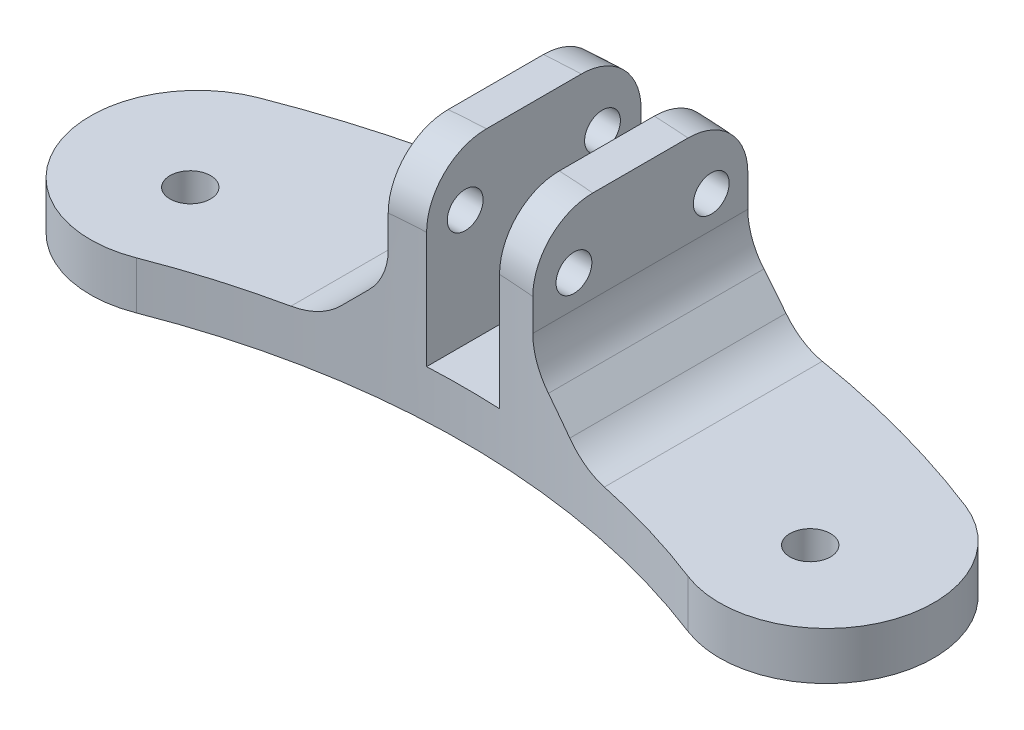
SolidWorks part; units mm, degrees
ref_plane "Front Plane" through (0, 0, 0) normal (0, 0, 1) x (1, 0, 0)
ref_plane "Top Plane" through (0, 0, 0) normal (0, 1, 0) x (1, 0, 0)
ref_plane "Right Plane" through (0, 0, 0) normal (1, 0, 0) x (0, 0, -1)
sketch "Sketch1" plane through (0, 0, 0) normal (0, 1, 0) x (1, 0, 0)
  line L0 (0, 0) -> (0, 66.7905) construction
  line L1 (-25.965, 66.7905) -> (25.965, 66.7905) construction
  line L2 (0, 63.75) -> (0, 81.7) construction
  line L3 (-29.6029, 76.1483) -> (-23.0989, 59.418) construction
  circle A1 centre (-25.965, 66.7905) radius 1.7
  circle A2 centre (25.965, 66.7905) radius 1.7
  arc A3 (-23.0989, 59.418) -> (23.0989, 59.418) centre (0, 0) cw
  arc A4 (-29.6029, 76.1483) -> (29.6029, 76.1483) centre (0, 0) cw
  arc A5 (-29.6029, 76.1483) -> (-23.0989, 59.418) centre (-26.3509, 67.7832) ccw
  arc A6 (29.6029, 76.1483) -> (23.0989, 59.418) centre (26.3509, 67.7832) cw
  point P7 (0, 66.7905)
  point P17 (0, 0)
  dimension "D1" = 51.93
  dimension "D3" = 3.4
  dimension "D4" = 63.75
  dimension "D2" = 71.66
  dimension "D5" = 17.95
extrude "Boss-Extrude1" add sketch "Sketch1" along normal blind 18.75
sketch "Sketch2" plane through (0, 0, 0) normal (0, 0, 1) x (1, 0, 0)
  line L0 (23.0989, 18.75) -> (-23.0989, 18.75) construction
  line L1 (-35.3259, 18.75) -> (-6.055, 18.75)
  line L2 (-35.3259, 18.75) -> (-35.3259, 4)
  line L3 (-35.3259, 4) -> (-6.055, 4)
  line L4 (-6.055, 18.75) -> (-6.055, 4)
  line L5 (35.3259, 18.75) -> (6.055, 18.75)
  line L6 (35.3259, 18.75) -> (35.3259, 4)
  line L7 (35.3259, 4) -> (6.055, 4)
  line L8 (6.055, 18.75) -> (6.055, 4)
  line L9 (-3.055, 18.75) -> (3.055, 18.75)
  line L10 (-3.055, 18.75) -> (-3.055, 4)
  line L11 (-3.055, 4) -> (3.055, 4)
  line L12 (3.055, 18.75) -> (3.055, 4)
  line L13 (0, 18.75) -> (0, 4) construction
  dimension "D1" = 4
  dimension "D2" = 6.11
  dimension "D3" = 3
extrude "Cut-Extrude1" cut sketch "Sketch2" against normal through all
chamfer "Chamfer1" distance 5 angle 45 2 edges at (-6.055, 4, -72.4686) (6.055, 4, -72.4686)
fillet "Fillet1" radius 5 4 edges at (11.055, 4, -71.8664) (6.055, 9, -72.4686) (-11.055, 4, -71.8664) (-6.055, 9, -72.4686)
sketch "Sketch4" plane through (3.055, 0, 0) normal (-1, 0, 0) x (0, 0, 1)
  line L0 (-78.4098, 13.75) -> (-66.9098, 13.75) construction
  line L1 (-81.6429, 18.75) -> (-63.6768, 18.75) construction
  line L2 (-72.6598, 18.75) -> (-72.6598, 13.75) construction
  line L3 (-81.6429, 4) -> (-63.6768, 4) construction
  circle A0 centre (-78.4098, 13.75) radius 1.5
  circle A1 centre (-66.9098, 13.75) radius 1.5
  point P4 (-72.6598, 18.75)
  point P5 (0, 0)
  point P10 (-78.1963, 15.1114)
  point P11 (0, 0)
  point P14 (0, 0)
  dimension "D1" = 3
  dimension "D2" = 3
  dimension "D3" = 5
  dimension "D4" = 11.5
extrude "Cut-Extrude2" cut sketch "Sketch4" against normal through all both and the other way through all
fillet "Fillet2" radius 5 4 edges at (4.5558, 18.75, -81.5729) (-4.5558, 18.75, -81.5729) (4.5563, 18.75, -63.587) (-4.5563, 18.75, -63.587)
